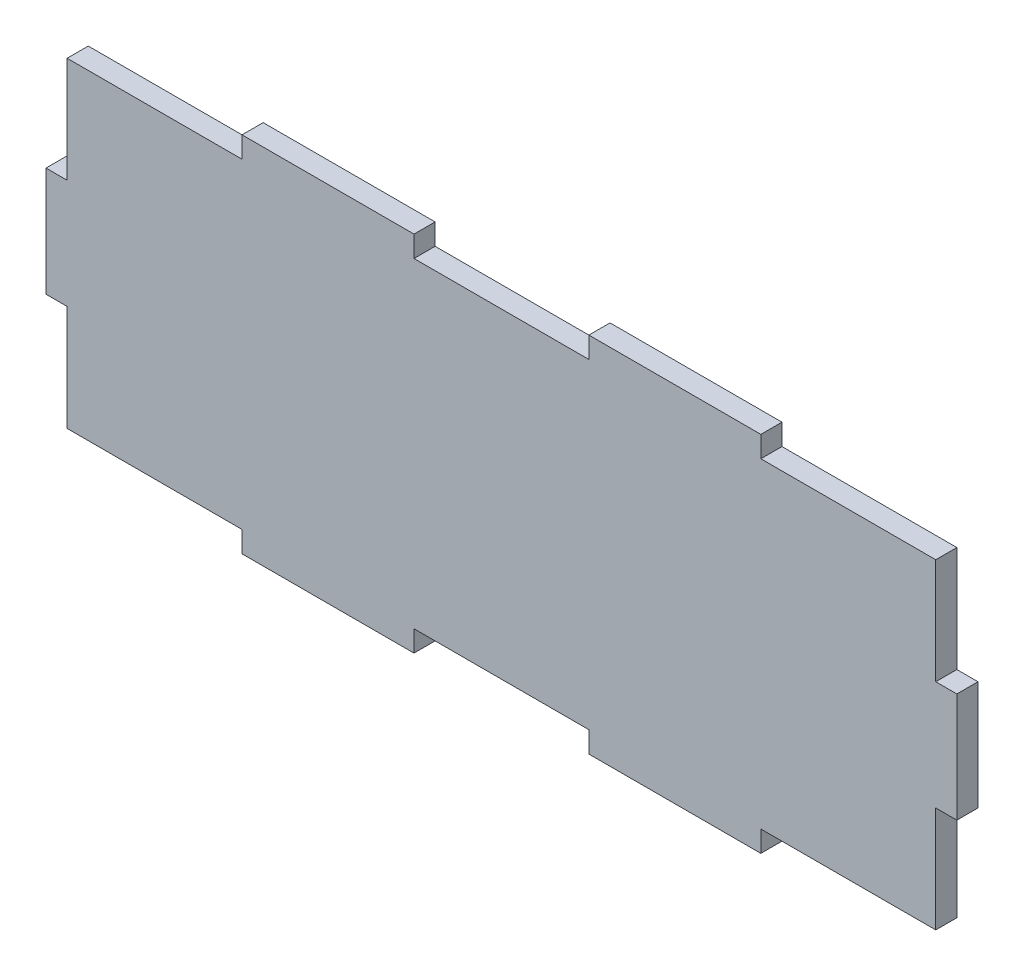
SolidWorks part; units mm, degrees
material "Бальса"
ref_plane "Спереди" through (0, 0, 0) normal (0, 0, 1) x (1, 0, 0)
ref_plane "Сверху" through (0, 0, 0) normal (0, 1, 0) x (1, 0, 0)
ref_plane "Справа" through (0, 0, 0) normal (1, 0, 0) x (0, 0, -1)
sketch "Эскиз1" plane through (0, 0, 0) normal (0, 0, 1) x (1, 0, 0)
  line L1 (0, 0) -> (238.4, 0)
  line L2 (0, 0) -> (0, 88)
  line L3 (0, 88) -> (238.4, 88)
  line L4 (238.4, 0) -> (238.4, 88)
  dimension "D1" = 88
  dimension "D2" = 238.4
extrude "Бобышка-Вытянуть1" add sketch "Эскиз1" along normal blind 5.8
sketch "Эскиз2" plane through (0, 0, 5.8) normal (0, 0, 1) x (1, 0, 0)
  line L0 (0, 88) -> (0, 0) construction
  line L1 (0, 59) -> (-5.8, 59)
  line L2 (0, 59) -> (0, 29)
  line L3 (0, 29) -> (-5.8, 29)
  line L4 (-5.8, 59) -> (-5.8, 29)
  line L5 (238.4, 0) -> (238.4, 88) construction
  line L6 (238.4, 59) -> (244.2, 59)
  line L7 (238.4, 59) -> (238.4, 29)
  line L8 (238.4, 29) -> (244.2, 29)
  line L9 (244.2, 59) -> (244.2, 29)
  line L10 (238.4, 88) -> (0, 88) construction
  line L11 (48, 88) -> (95.2, 88)
  line L12 (48, 88) -> (48, 93.8)
  line L13 (48, 93.8) -> (95.2, 93.8)
  line L14 (95.2, 88) -> (95.2, 93.8)
  line L15 (0, 0) -> (238.4, 0) construction
  line L16 (143.2, 88) -> (190.4, 88)
  line L17 (143.2, 88) -> (143.2, 93.8)
  line L18 (143.2, 93.8) -> (190.4, 93.8)
  line L19 (190.4, 88) -> (190.4, 93.8)
  line L20 (48, 0) -> (95.2, 0)
  line L21 (48, 0) -> (48, -5.8)
  line L22 (48, -5.8) -> (95.2, -5.8)
  line L23 (95.2, 0) -> (95.2, -5.8)
  line L25 (143.2, 0) -> (190.4, 0)
  line L26 (143.2, 0) -> (143.2, -5.8)
  line L27 (143.2, -5.8) -> (190.4, -5.8)
  line L28 (190.4, 0) -> (190.4, -5.8)
  point P32 (-2.9, 29)
  dimension "D1" = 29
  dimension "D2" = 29
  dimension "D3" = 48
  dimension "D4" = 48
  dimension "D5" = 48
  dimension "D6" = 5.8
extrude "Бобышка-Вытянуть2" add sketch "Эскиз2" against normal up to surface (5.8 mm away) up to face at (119.2, 44, 0)
